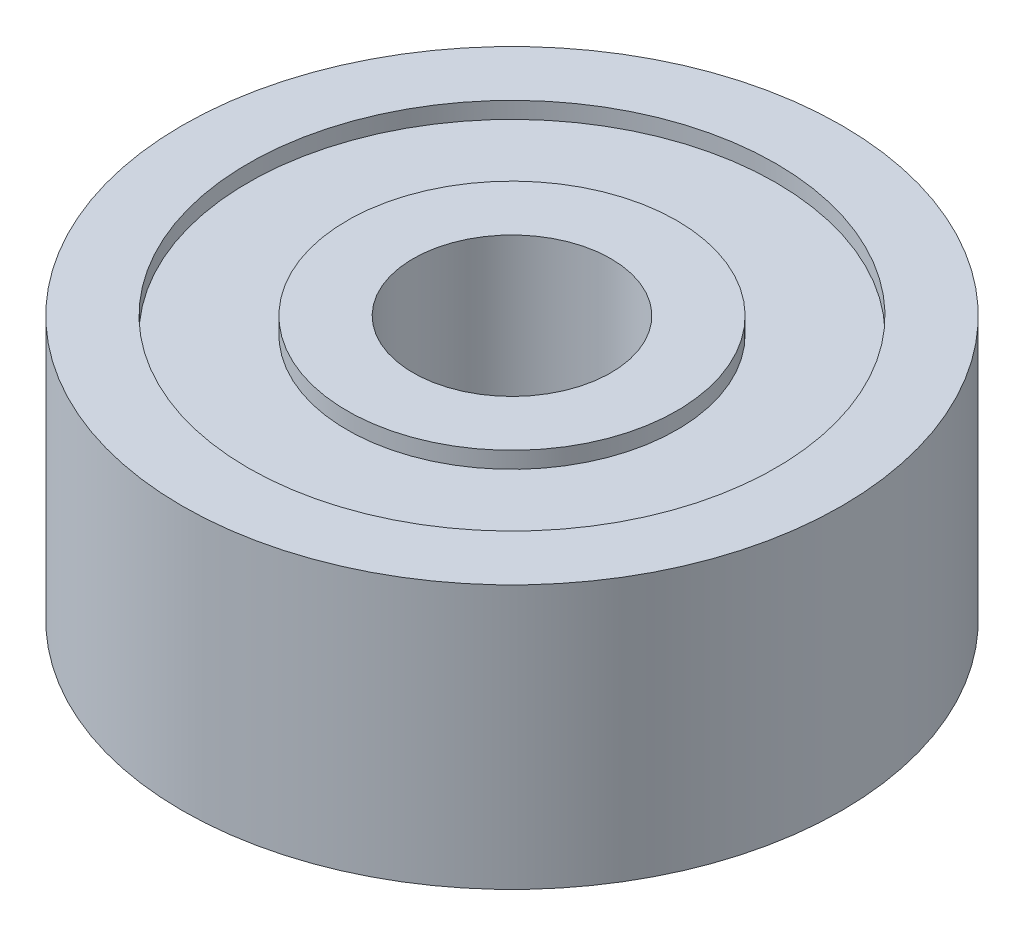
SolidWorks part; units mm, degrees
ref_plane "Front Plane" through (0, 0, 0) normal (0, 0, 1) x (1, 0, 0)
ref_plane "Top Plane" through (0, 0, 0) normal (0, 1, 0) x (1, 0, 0)
ref_plane "Right Plane" through (0, 0, 0) normal (1, 0, 0) x (0, 0, -1)
sketch "Sketch1" plane through (0, 0, 0) normal (0, 0, 1) x (1, 0, 0)
  line L0 (0, 0) -> (0, 4) construction
  line L1 (1.5, 4) -> (1.5, 0)
  line L2 (2.5, 0) -> (2.5, 0.25)
  line L3 (2.5, 0.25) -> (4, 0.25)
  line L4 (4, 0.25) -> (4, 0)
  line L5 (4, 0) -> (5, 0)
  line L6 (5, 0) -> (5, 4)
  line L7 (0, 2) -> (5, 2) construction
  line L8 (1.5, 0) -> (2.5, 0)
  line L9 (1.5, 4) -> (2.5, 4)
  line L10 (4, 4) -> (5, 4)
  line L11 (4, 3.75) -> (4, 4)
  line L12 (2.5, 3.75) -> (4, 3.75)
  line L13 (2.5, 4) -> (2.5, 3.75)
  point P18 (1.5, 2)
  dimension "D1" = 4
  dimension "D2" = 5
  dimension "D3" = 1
  dimension "D4" = 1
  dimension "D5" = 1.5
  dimension "D6" = 0.25
revolve "Revolve1" add sketch "Sketch1" angle 360 about L0
